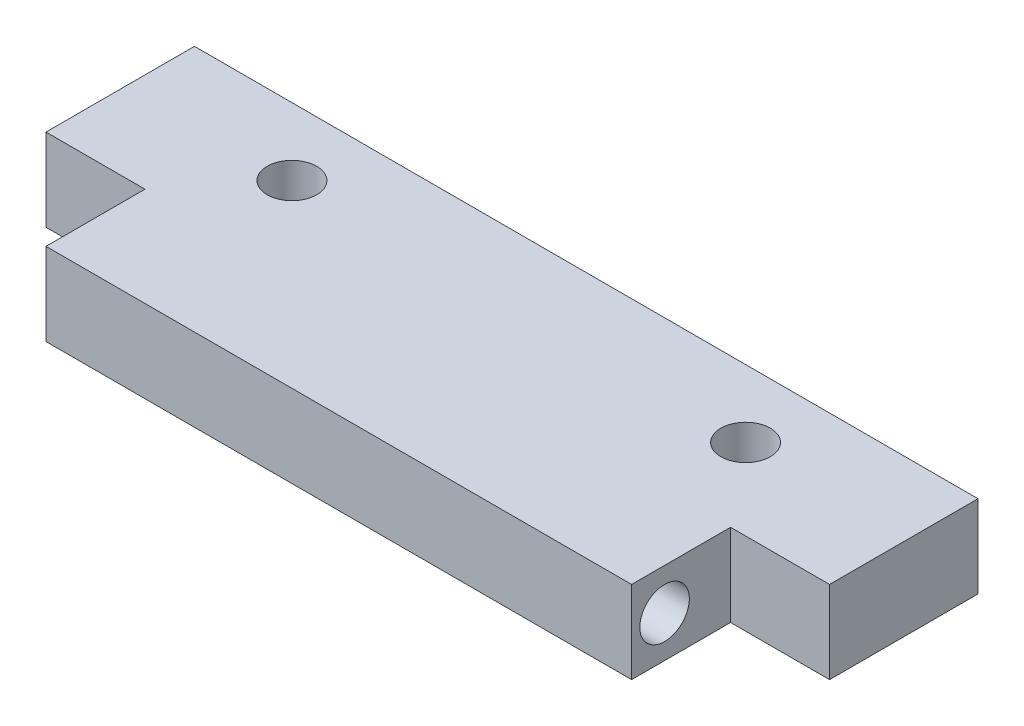
SolidWorks part; units mm, degrees
ref_plane "Front Plane" through (0, 0, 0) normal (0, 0, 1) x (1, 0, 0)
ref_plane "Top Plane" through (0, 0, 0) normal (0, 1, 0) x (1, 0, 0)
ref_plane "Right Plane" through (0, 0, 0) normal (1, 0, 0) x (0, 0, -1)
sketch "Sketch2" plane through (0, 0, 0) normal (0, 1, 0) x (1, 0, 0)
  line L0 (-70.8875, 28.609) -> (-23.3875, 28.609)
  line L9 (-23.3875, 28.609) -> (-23.3875, 19.609)
  line L14 (-70.8875, 28.609) -> (-70.8875, 19.609)
  line L16 (-70.8875, 19.609) -> (-64.8875, 19.609)
  line L17 (-64.8875, 19.609) -> (-64.8875, 13.609)
  line L18 (-23.3875, 19.609) -> (-29.3875, 19.609)
  line L19 (-29.3875, 19.609) -> (-29.3875, 13.609)
  line L20 (-64.8875, 13.609) -> (-29.3875, 13.609)
  circle A0 centre (-60.8875, 24.5186) radius 1.5
  circle A1 centre (-33.3875, 24.5186) radius 1.5
  point P13 (-47.1375, 24.5186)
extrude "Boss-Extrude1" add sketch "Sketch2" along normal blind 5
sketch "Sketch4" plane through (-64.8875, 0, 0) normal (-1, 0, 0) x (0, 0, 1)
  circle A0 centre (-15.609, 2.5) radius 1.5
  point P6 (-15.6732, 2.5)
extrude "Cut-Extrude1" cut sketch "Sketch4" against normal through all contours A0
